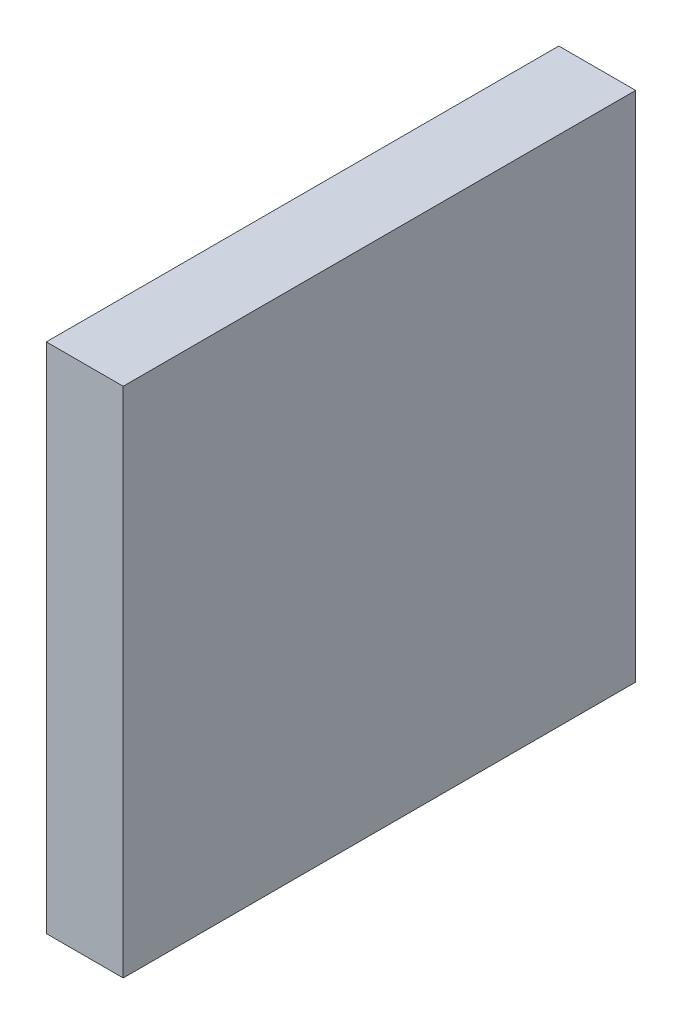
SolidWorks part; units mm, degrees
ref_plane "Alzado" through (0, 0, 0) normal (0, 0, 1) x (1, 0, 0)
ref_plane "Planta" through (0, 0, 0) normal (0, 1, 0) x (1, 0, 0)
ref_plane "Vista lateral" through (0, 0, 0) normal (1, 0, 0) x (0, 0, -1)
sketch "Croquis1" plane through (0, 0, 0) normal (1, 0, 0) x (0, 0, -1)
  line L1 (0, 0) -> (100, 0)
  line L2 (0, 0) -> (0, 100)
  line L3 (0, 100) -> (100, 100)
  line L4 (100, 0) -> (100, 100)
  dimension "D1" = 100
  dimension "D2" = 100
extrude "Saliente-Extruir1" add sketch "Croquis1" along normal blind 15
